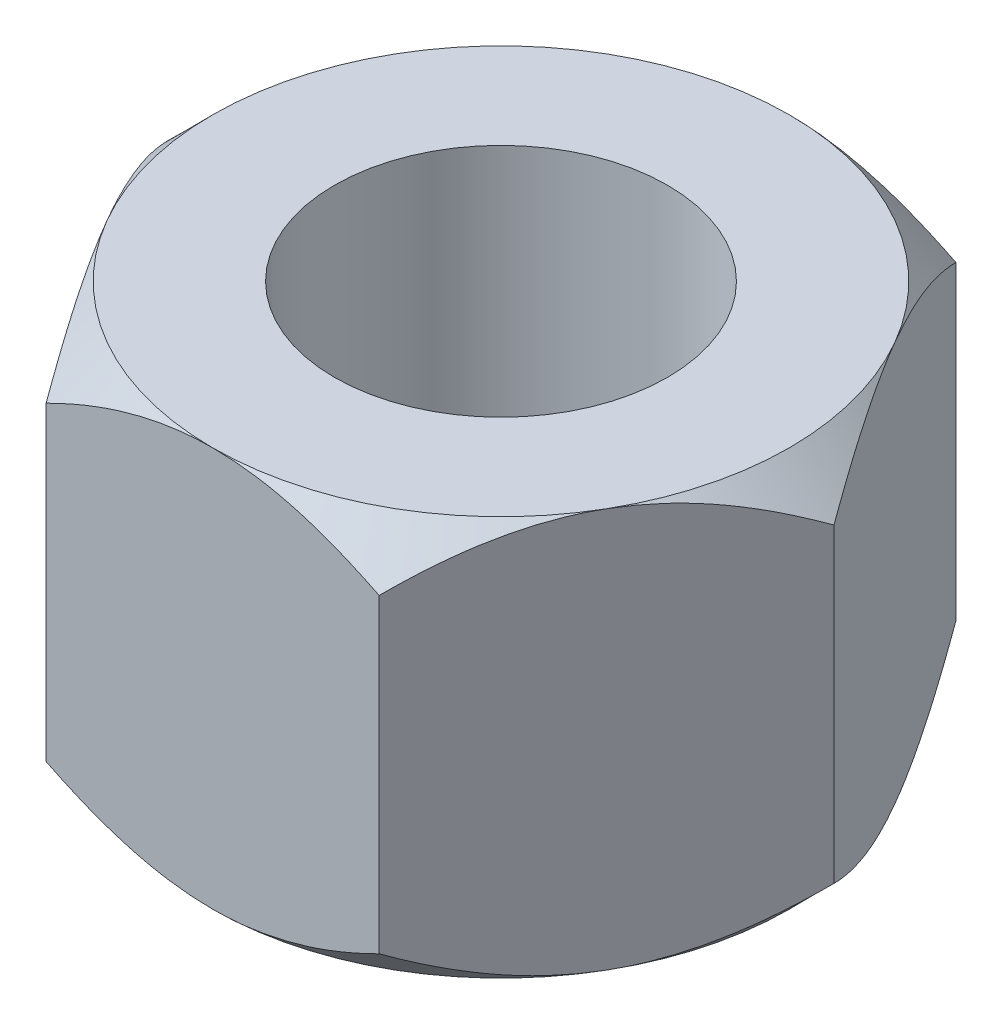
SolidWorks part; units mm, degrees
material "Plain Carbon Steel"
ref_plane "Front Plane" through (0, 0, 0) normal (0, 0, 1) x (1, 0, 0)
ref_plane "Top Plane" through (0, 0, 0) normal (0, 1, 0) x (1, 0, 0)
ref_plane "Right Plane" through (0, 0, 0) normal (1, 0, 0) x (0, 0, -1)
sketch "Sketch1" plane through (0, 0, 0) normal (0, 1, 0) x (1, 0, 0)
  line L1 (-1.25, -2.1651) -> (1.25, -2.1651)
  line L2 (1.25, -2.1651) -> (2.5, 0)
  line L3 (2.5, 0) -> (1.25, 2.1651)
  line L4 (1.25, 2.1651) -> (-1.25, 2.1651)
  line L5 (-1.25, 2.1651) -> (-2.5, 0)
  line L6 (-2.5, 0) -> (-1.25, -2.1651)
  circle A0 centre (0, 0) radius 2.1651 construction
  circle A1 centre (0, 0) radius 1.25
  dimension "D2" = 2.5
  dimension "D1" = 5
extrude "Boss-Extrude1" add sketch "Sketch1" along normal blind 3
sketch "Sketch2" plane through (0, 3, 0) normal (0, 1, 0) x (1, 0, 0)
  line L0 (-1.25, 2.1651) -> (-2.5, 0) construction
  circle A0 centre (0, 0) radius 2.1651
extrude "Cut-Extrude1" cut sketch "Sketch2" against normal through all draft 45 flip side to cut
sketch "Sketch3" plane through (0, 0, 0) normal (0, -1, 0) x (1, 0, 0)
  line L0 (-2.5, 0) -> (-1.25, 2.1651) construction
  circle A0 centre (0, 0) radius 2.1651
extrude "Cut-Extrude2" cut sketch "Sketch3" against normal through all draft 45 flip side to cut
